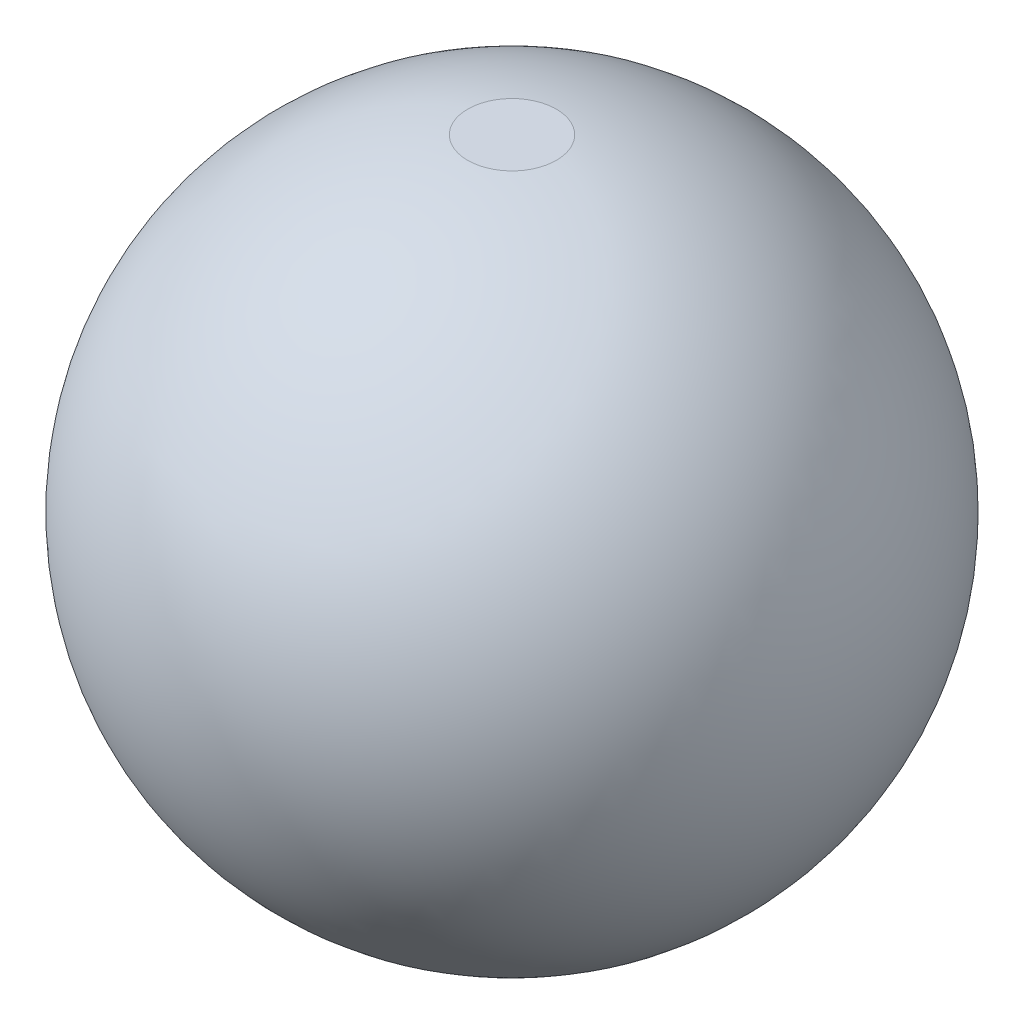
SolidWorks part; units mm, degrees
ref_plane "前视基准面" through (0, 0, 0) normal (0, 0, 1) x (1, 0, 0)
ref_plane "上视基准面" through (0, 0, 0) normal (0, 1, 0) x (1, 0, 0)
ref_plane "右视基准面" through (0, 0, 0) normal (1, 0, 0) x (0, 0, -1)
sketch "草图1" plane through (0, 0, 0) normal (0, 1, 0) x (1, 0, 0)
  line L0 (0, 1.1) -> (0, -1.1)
  arc A0 (0, 1.1) -> (0, -1.1) centre (0, 0) ccw
  point P6 (0, 0)
  dimension "D1" = 2.2
revolve "旋转1" add sketch "草图1" angle 360 about L0
ref_plane "基准面1" through (0, 1.09, 0) normal (0, 1, 0) x (1, 0, 0)
sketch "草图2" plane through (0, 1.09, 0) normal (0, 1, 0) x (1, 0, 0)
  circle A0 centre (0, 0) radius 0.5153
extrude "切除-拉伸1" cut sketch "草图2" along normal blind 10
